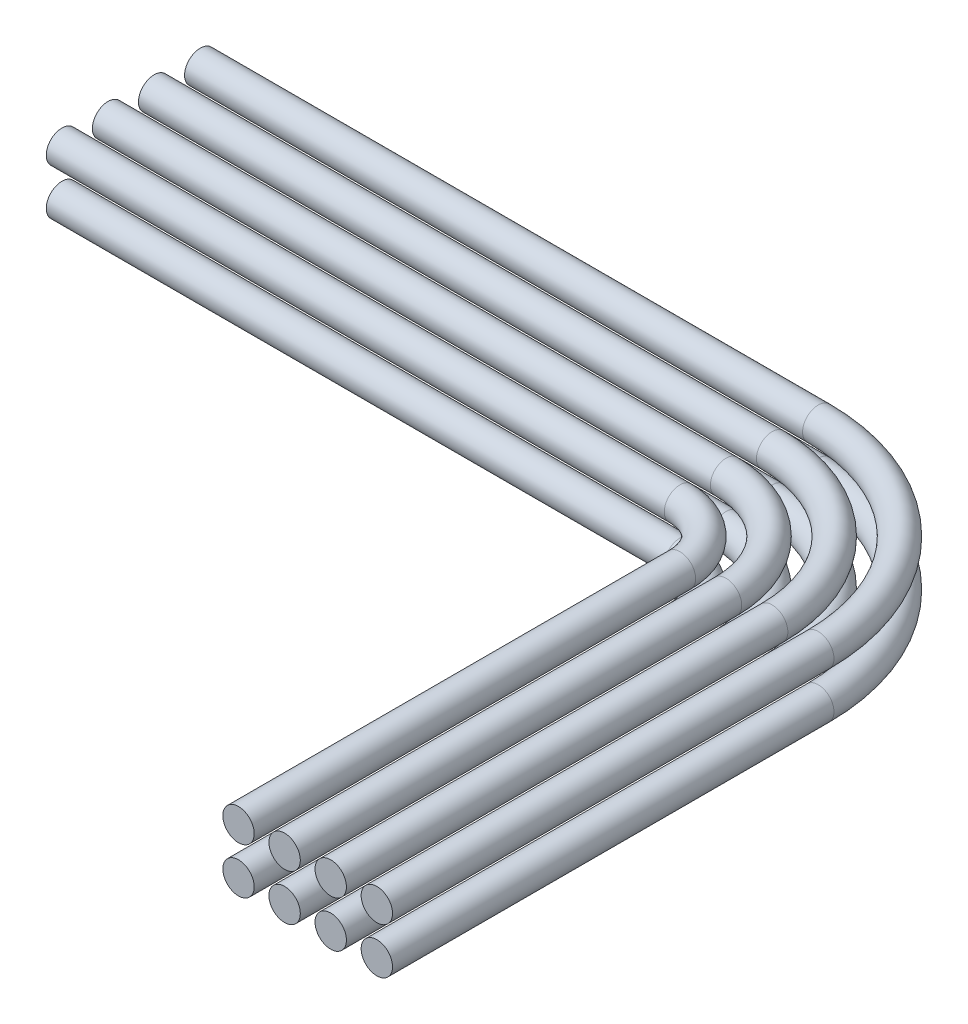
SolidWorks part; units mm, degrees
ref_plane "Front Plane" through (0, 0, 0) normal (0, 0, 1) x (1, 0, 0)
ref_plane "Top Plane" through (0, 0, 0) normal (0, 1, 0) x (1, 0, 0)
ref_plane "Right Plane" through (0, 0, 0) normal (1, 0, 0) x (0, 0, -1)
sketch "Sketch1" plane through (0, 0, 0) normal (0, 1, 0) x (1, 0, 0)
  line L0 (0, 0) -> (63, 0)
  line L1 (83, -20) -> (83, -65)
  line L2 (0, -4.7) -> (63, -4.7)
  line L3 (78.3, -20) -> (78.3, -65)
  line L4 (0, -4.7) -> (0, 0) construction
  line L5 (83, -65) -> (78.3, -65) construction
  line L6 (0, -4.7) -> (0, -9.4) construction
  line L7 (0, -9.4) -> (0, -14.1) construction
  line L8 (78.3, -65) -> (73.6, -65) construction
  line L9 (73.6, -65) -> (68.9, -65) construction
  line L10 (0, -9.4) -> (63, -9.4)
  line L11 (73.6, -20) -> (73.6, -65)
  line L12 (68.9, -65) -> (68.9, -20)
  line L13 (63, -14.1) -> (0, -14.1)
  line L14 (63, 0) -> (63, -14.1) construction
  line L15 (68.9, -20) -> (83, -20) construction
  arc A0 (63, -4.7) -> (78.3, -20) centre (63, -20) cw
  arc A1 (63, 0) -> (83, -20) centre (63, -20) cw
  arc A2 (63, -9.4) -> (73.6, -20) centre (63, -20) cw
  arc A3 (68.9, -20) -> (63, -14.1) centre (63, -20) ccw
  point P11 (83, 0)
  dimension "D5" = 20
  dimension "D1" = 4.7
  dimension "D2" = 63
  dimension "D3" = 65
ref_plane "Plane1" through (0, 0, 0) normal (1, 0, 0) x (0, 0, -1)
sketch "Sketch2" plane through (0, 0, 0) normal (1, 0, 0) x (0, 0, -1)
  circle A0 centre (0, 0) radius 1.6
  circle A1 centre (-4.7, 0) radius 1.6
  circle A2 centre (-9.4, 0) radius 1.6
  circle A3 centre (-14.1, 0) radius 1.6
  dimension "D1" = 3.2
sweep "Sweep1" add profiles "Sketch2" path "Sketch1"
sketch "Sketch3" plane through (0, 0, 0) normal (1, 0, 0) x (0, 0, -1)
  line L0 (0, 0) -> (0, 4.7) construction
  dimension "D1" = 4.7
pattern_linear "LPattern1" count 2 spacing 4.7 along (0, 1, 0) of "Sweep1"
